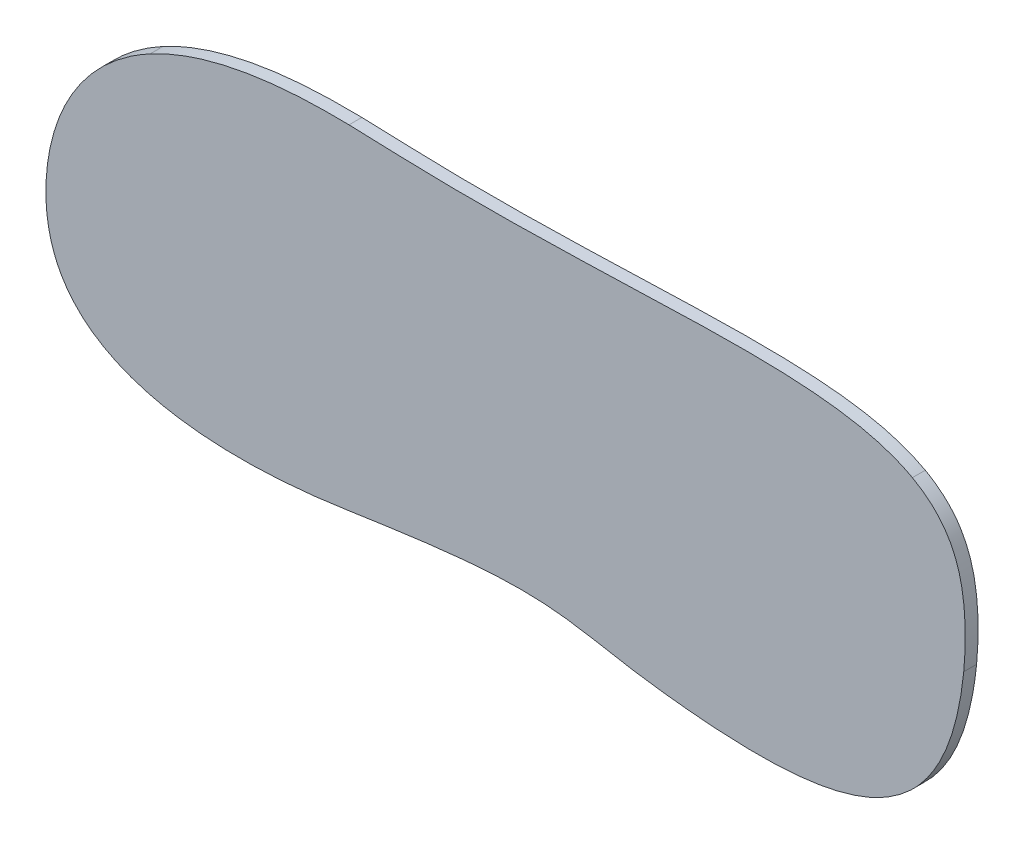
SolidWorks part; units mm, degrees
ref_plane "Front Plane" through (0, 0, 0) normal (0, 0, 1) x (1, 0, 0)
ref_plane "Top Plane" through (0, 0, 0) normal (0, 1, 0) x (1, 0, 0)
ref_plane "Right Plane" through (0, 0, 0) normal (1, 0, 0) x (0, 0, -1)
sketch "Sketch1" plane through (0, 0, 0) normal (0, 0, 1) x (1, 0, 0)
  spline S18 degree 3 poles (3988.5531, -515.6953) (-531.3605, -251.9518) (37.4399, -132.3205) (42.5071, 4.3207) (42.5126, 5.3656) (42.4428, 7.4577) (42.3677, 8.5023) (42.1143, 10.5641) (41.9371, 11.5844) (41.4308, 13.593) (41.0992, 14.582) (40.2181, 16.5096) (39.6851, 17.4106) (38.7365, 18.6609) (38.3954, 19.0608) (37.6626, 19.8262) (37.2758, 20.1865) (-13.491, 62.6977) (-324.3005, -240.8462) (2280.8109, 3326.2357) knots -16.110576 -16.110576 -16.110576 -16.110576 0.125 0.125 0.25 0.25 0.375 0.375 0.5 0.5 0.625 0.625 0.75 0.75 0.8125 0.8125 0.875 0.875 8.693513 8.693513 8.693513 8.693513 only from (42.2546, 0.1475) to (34.2708, 22.2985)
  spline S19 degree 3 poles (-995.4974, -3840.5557) (80.969, -167.3527) (79.8348, 4.3374) (30.8995, 23.8249) (30.0291, 24.1168) (27.3844, 24.8841) (25.5767, 25.2516) (21.9096, 25.8146) (20.0753, 26.0052) (16.406, 26.2795) (14.571, 26.362) (10.9003, 26.4602) (9.0648, 26.4753) (5.3933, 26.4641) (3.5574, 26.4375) (-1.9506, 26.3227) (-5.6229, 26.1998) (-12.9676, 25.9541) (-16.6399, 25.8303) (-23.9842, 25.6386) (-27.6562, 25.5704) (-34.9999, 25.5307) (-38.6714, 25.5591) (-43.2605, 25.6755) (-44.1783, 25.7028) (-46.0139, 25.766) (-46.9317, 25.8019) (-140.0218, 29.3828) (-232.2287, 25.5725) (-343.1162, -3956.4698) knots -1.72518 -1.72518 -1.72518 -1.72518 0.03125 0.03125 0.0625 0.0625 0.125 0.125 0.1875 0.1875 0.25 0.25 0.3125 0.3125 0.375 0.375 0.5 0.5 0.625 0.625 0.75 0.75 0.875 0.875 0.90625 0.90625 0.9375 0.9375 4.075987 4.075987 4.075987 4.075987 only from (34.2708, 22.2985) to (-53.3562, 26.0089)
  spline S20 degree 3 poles (208.7179, 4006.1361) (166.3174, -194.5618) (50.5587, 32.297) (-63.9928, 25.732) (-66.6375, 25.455) (-70.5761, 24.7953) (-71.8788, 24.5352) (-74.4519, 23.9263) (-75.7237, 23.5773) (-163.7242, -4.4509) (-171.4487, -270.9444) (915.6669, -3846.9245) knots -10.275125 -10.275125 -10.275125 -10.275125 0.25 0.25 0.5 0.5 0.625 0.625 0.75 0.75 9.389686 9.389686 9.389686 9.389686 only from (-53.3562, 26.0089) to (-84.2859, 20.1047)
  spline S21 degree 3 poles (-2018.6771, 3502.84) (492.5303, -411.3425) (3.5787, 93.8774) (-90.2301, 16.0437) (-90.6487, 15.677) (-91.461, 14.9254) (-91.8555, 14.5398) (-93.0037, 13.3533) (-93.7223, 12.5228) (-95.0634, 10.7809) (-95.686, 9.8696) (-96.5451, 8.4396) (-96.8182, 7.9534) (-97.3329, 6.9725) (-97.5754, 6.4764) (-228.4337, -281.6073) (4361.4767, -2372.7077) (-418.3441, -884.0311) knots -13.38136 -13.38136 -13.38136 -13.38136 0.25 0.25 0.3125 0.3125 0.375 0.375 0.5 0.5 0.625 0.625 0.6875 0.6875 0.75 0.75 36.575619 36.575619 36.575619 36.575619 only from (-84.2859, 20.1047) to (-99.8531, -0.3074)
  spline S22 degree 3 poles (3886.9027, 199.422) (631.1588, 208.6072) (-91.8244, 116.3867) (-100.5286, -5.8158) (-100.5371, -7.1993) (-100.4025, -8.9345) (-100.3683, -9.2819) (-100.2834, -9.9772) (-100.2326, -10.326) (-100.0552, -11.3631) (-99.9033, -12.0442) (-99.5256, -13.3836) (-99.2997, -14.0419) (-98.765, -15.333) (-98.4533, -15.97) (-97.4092, -17.7896) (-96.566, -18.8911) (-95.0908, -20.3837) (-94.5625, -20.8554) (-93.4696, -21.724) (-92.9017, -22.1248) (-91.7292, -22.8687) (-91.1243, -23.2117) (-89.882, -23.8465) (-89.2425, -24.1391) (-13.9683, -55.2038) (174.5873, 240.8851) (-1172.2552, -3868.3937) knots -10.819695 -10.819695 -10.819695 -10.819695 0.125 0.125 0.25 0.25 0.28125 0.28125 0.3125 0.3125 0.375 0.375 0.4375 0.4375 0.5 0.5 0.625 0.625 0.6875 0.6875 0.75 0.75 0.8125 0.8125 0.875 0.875 8.073708 8.073708 8.073708 8.073708 only from (-99.8531, -0.3074) to (-84.6127, -25.7399)
  spline S23 degree 3 poles (362.7777, 3944.3717) (-203.0271, 186.3217) (-157.9272, -13.4143) (-79.5112, -26.785) (-78.2197, -26.9519) (-74.3235, -27.3271) (-71.7178, -27.4101) (-66.5009, -27.3454) (-63.9001, -27.1967) (-60.0127, -26.8423) (-58.7189, -26.7021) (20.565, -16.8605) (90.6215, 80.9473) (534.8903, -3977.058) knots -7.391911 -7.391911 -7.391911 -7.391911 0.125 0.125 0.25 0.25 0.5 0.5 0.75 0.75 0.875 0.875 8.420809 8.420809 8.420809 8.420809 only from (-84.6127, -25.7399) to (-53.5558, -26.0073)
  spline S24 degree 3 poles (-1025.0306, 3835.3973) (-317.1538, -178.3206) (-187.4318, -42.4568) (-39.2648, -24.0452) (-37.2174, -23.8145) (-33.1154, -23.4404) (-31.0607, -23.2966) (-26.9381, -23.1646) (-24.8803, -23.1794) (-21.8071, -23.3778) (-20.7847, -23.4732) (-18.7437, -23.7193) (-17.725, -23.8701) (-15.6901, -24.2058) (-14.6752, -24.3901) (-12.6457, -24.7605) (-11.631, -24.9462) (-9.5982, -25.2959) (-8.5801, -25.4599) (200.5902, -55.9492) (510.4804, 544.0571) (-5.8811, -3975.0908) knots -8.680654 -8.680654 -8.680654 -8.680654 0.25 0.25 0.375 0.375 0.5 0.5 0.625 0.625 0.6875 0.6875 0.75 0.75 0.8125 0.8125 0.875 0.875 0.9375 0.9375 13.684087 13.684087 13.684087 13.684087 only from (-53.5558, -26.0073) to (-4.4904, -26.0102)
  spline S25 degree 3 poles (43.9775, 3965.8408) (-189.2694, 72.003) (-97.854, -17.9584) (2.1761, -26.6805) (3.8468, -26.7995) (7.1947, -26.9634) (8.8693, -27.0083) (12.2156, -26.9954) (13.8879, -26.9379) (16.3946, -26.7436) (17.2302, -26.6606) (18.8895, -26.4528) (19.7145, -26.3279) (22.173, -25.8793) (23.7904, -25.483) (26.1705, -24.6816) (26.9602, -24.3778) (28.4922, -23.7) (29.2362, -23.3259) (95.5053, 14.6548) (-38.0951, 371.6393) (-1889.0186, 3483.0447) knots -7.244014 -7.244014 -7.244014 -7.244014 0.125 0.125 0.25 0.25 0.375 0.375 0.5 0.5 0.5625 0.5625 0.625 0.625 0.75 0.75 0.8125 0.8125 0.875 0.875 6.564915 6.564915 6.564915 6.564915 only from (-4.4904, -26.0102) to (33.9719, -19.949)
  spline S26 degree 3 poles (-3200.142, 2326.1143) (-415.8893, 144.5472) (-14.9525, -80.3999) (36.4491, -17.1934) (36.9876, -16.4363) (38.4691, -14.0668) (39.2543, -12.4018) (40.2153, -9.8128) (40.4993, -8.9345) (41.0038, -7.1511) (41.2235, -6.248) (68.087, 120.9335) (-430.6853, 339.8888) (4012.3325, -312.8053) knots -10.754391 -10.754391 -10.754391 -10.754391 0.125 0.125 0.25 0.25 0.5 0.5 0.625 0.625 0.75 0.75 18.174706 18.174706 18.174706 18.174706 only from (33.9719, -19.949) to (42.2546, 0.1475)
  spline S27 degree 3 poles (42.2546, 0.1475) (42.3575, 1.1897) (42.4297, 2.2327) (42.5071, 4.3207) (42.5126, 5.3656) (42.4428, 7.4577) (42.3677, 8.5023) (42.1143, 10.5641) (41.9371, 11.5844) (41.4308, 13.593) (41.0992, 14.582) (40.2181, 16.5096) (39.6851, 17.4106) (38.7365, 18.6609) (38.3954, 19.0608) (37.6626, 19.8262) (37.2758, 20.1865) (36.068, 21.1979) (35.1962, 21.7838) (34.2708, 22.2985) knots 0 0 0 0 0.125 0.125 0.25 0.25 0.375 0.375 0.5 0.5 0.625 0.625 0.75 0.75 0.8125 0.8125 0.875 0.875 1 1 1 1
  spline S28 degree 3 poles (34.2708, 22.2985) (33.4509, 22.7546) (32.6103, 23.1436) (30.8995, 23.8249) (30.0291, 24.1168) (27.3844, 24.8841) (25.5767, 25.2516) (21.9096, 25.8146) (20.0753, 26.0052) (16.406, 26.2795) (14.571, 26.362) (10.9003, 26.4602) (9.0648, 26.4753) (5.3933, 26.4641) (3.5574, 26.4375) (-1.9506, 26.3227) (-5.6229, 26.1998) (-12.9676, 25.9541) (-16.6399, 25.8303) (-23.9842, 25.6386) (-27.6562, 25.5704) (-34.9999, 25.5307) (-38.6714, 25.5591) (-43.2605, 25.6755) (-44.1783, 25.7028) (-46.0139, 25.766) (-46.9317, 25.8019) (-49.6849, 25.9078) (-51.5205, 25.9755) (-53.3562, 26.0089) knots 0 0 0 0 0.03125 0.03125 0.0625 0.0625 0.125 0.125 0.1875 0.1875 0.25 0.25 0.3125 0.3125 0.375 0.375 0.5 0.5 0.625 0.625 0.75 0.75 0.875 0.875 0.90625 0.90625 0.9375 0.9375 1 1 1 1
  spline S29 degree 3 poles (-53.3562, 26.0089) (-56.0173, 26.0573) (-58.6772, 26.0366) (-63.9928, 25.732) (-66.6375, 25.455) (-70.5761, 24.7953) (-71.8788, 24.5352) (-74.4519, 23.9263) (-75.7237, 23.5773) (-79.4888, 22.3781) (-81.9328, 21.3786) (-84.2859, 20.1047) knots 0 0 0 0 0.25 0.25 0.5 0.5 0.625 0.625 0.75 0.75 1 1 1 1
  spline S30 degree 3 poles (-84.2859, 20.1047) (-86.2437, 19.0449) (-88.0893, 17.8199) (-90.2301, 16.0437) (-90.6487, 15.677) (-91.461, 14.9254) (-91.8555, 14.5398) (-93.0037, 13.3533) (-93.7223, 12.5228) (-95.0634, 10.7809) (-95.686, 9.8696) (-96.5451, 8.4396) (-96.8182, 7.9534) (-97.3329, 6.9725) (-97.5754, 6.4764) (-98.7148, 3.9679) (-99.3965, 1.8732) (-99.8531, -0.3074) knots 0 0 0 0 0.25 0.25 0.3125 0.3125 0.375 0.375 0.5 0.5 0.625 0.625 0.6875 0.6875 0.75 0.75 1 1 1 1
  spline S31 degree 3 poles (-99.8531, -0.3074) (-100.1405, -1.6798) (-100.332, -3.056) (-100.5286, -5.8158) (-100.5371, -7.1993) (-100.4025, -8.9345) (-100.3683, -9.2819) (-100.2834, -9.9772) (-100.2326, -10.326) (-100.0552, -11.3631) (-99.9033, -12.0442) (-99.5256, -13.3836) (-99.2997, -14.0419) (-98.765, -15.333) (-98.4533, -15.97) (-97.4092, -17.7896) (-96.566, -18.8911) (-95.0908, -20.3837) (-94.5625, -20.8554) (-93.4696, -21.724) (-92.9017, -22.1248) (-91.7292, -22.8687) (-91.1243, -23.2117) (-89.882, -23.8465) (-89.2425, -24.1391) (-87.2987, -24.9412) (-85.9686, -25.3775) (-84.6127, -25.7399) knots 0 0 0 0 0.125 0.125 0.25 0.25 0.28125 0.28125 0.3125 0.3125 0.375 0.375 0.4375 0.4375 0.5 0.5 0.625 0.625 0.6875 0.6875 0.75 0.75 0.8125 0.8125 0.875 0.875 1 1 1 1
  spline S32 degree 3 poles (-84.6127, -25.7399) (-83.3504, -26.0773) (-82.0766, -26.3476) (-79.5112, -26.785) (-78.2197, -26.9519) (-74.3235, -27.3271) (-71.7178, -27.4101) (-66.5009, -27.3454) (-63.9001, -27.1967) (-60.0127, -26.8423) (-58.7189, -26.7021) (-56.135, -26.3813) (-54.8452, -26.1968) (-53.5558, -26.0073) knots 0 0 0 0 0.125 0.125 0.25 0.25 0.5 0.5 0.75 0.75 0.875 0.875 1 1 1 1
  spline S33 degree 3 poles (-53.5558, -26.0073) (-49.478, -25.4081) (-45.4004, -24.8076) (-39.2648, -24.0452) (-37.2174, -23.8145) (-33.1154, -23.4404) (-31.0607, -23.2966) (-26.9381, -23.1646) (-24.8803, -23.1794) (-21.8071, -23.3778) (-20.7847, -23.4732) (-18.7437, -23.7193) (-17.725, -23.8701) (-15.6901, -24.2058) (-14.6752, -24.3901) (-12.6457, -24.7605) (-11.631, -24.9462) (-9.5982, -25.2959) (-8.5801, -25.4599) (-6.5388, -25.7574) (-5.5158, -25.891) (-4.4904, -26.0102) knots 0 0 0 0 0.25 0.25 0.375 0.375 0.5 0.5 0.625 0.625 0.6875 0.6875 0.75 0.75 0.8125 0.8125 0.875 0.875 0.9375 0.9375 1 1 1 1
  spline S34 degree 3 poles (-4.4904, -26.0102) (-2.8274, -26.2206) (-1.1609, -26.3895) (2.1761, -26.6805) (3.8468, -26.7995) (7.1947, -26.9634) (8.8693, -27.0083) (12.2156, -26.9954) (13.8879, -26.9379) (16.3946, -26.7436) (17.2302, -26.6606) (18.8895, -26.4528) (19.7145, -26.3279) (22.173, -25.8793) (23.7904, -25.483) (26.1705, -24.6816) (26.9602, -24.3778) (28.4922, -23.7) (29.2362, -23.3259) (31.3962, -22.0879) (32.7402, -21.1084) (33.9719, -19.949) knots 0 0 0 0 0.125 0.125 0.25 0.25 0.375 0.375 0.5 0.5 0.5625 0.5625 0.625 0.625 0.75 0.75 0.8125 0.8125 0.875 0.875 1 1 1 1
  spline S35 degree 3 poles (33.9719, -19.949) (34.6513, -19.3094) (35.2814, -18.6294) (36.4491, -17.1934) (36.9876, -16.4363) (38.4691, -14.0668) (39.2543, -12.4018) (40.2153, -9.8128) (40.4993, -8.9345) (41.0038, -7.1511) (41.2235, -6.248) (41.7975, -3.5304) (42.0721, -1.6995) (42.2546, 0.1475) knots 0 0 0 0 0.125 0.125 0.25 0.25 0.5 0.5 0.625 0.625 0.75 0.75 1 1 1 1
  dimension "D1" = 0.5
extrude "Boss-Extrude1" add sketch "Sketch1" along normal blind 2
